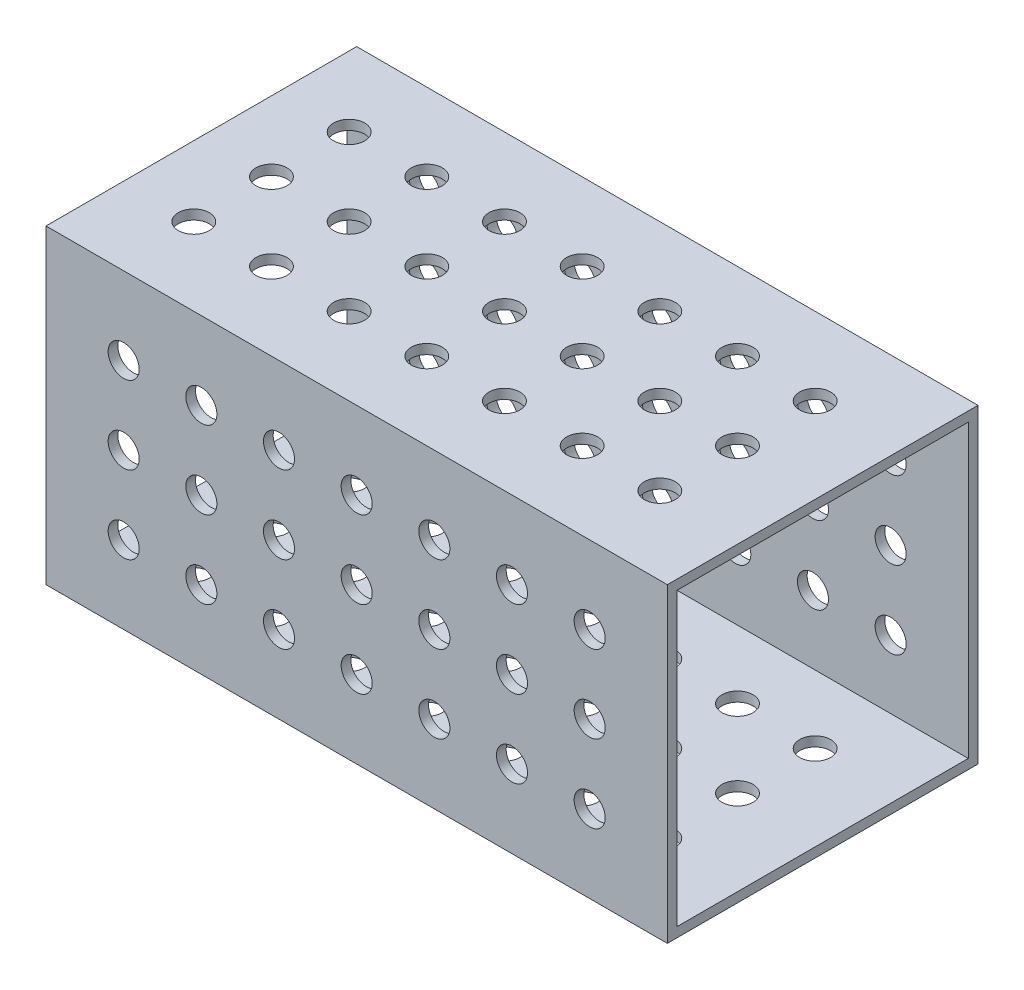
SolidWorks part; units mm, degrees
ref_plane "Front Plane" through (0, 0, 0) normal (0, 0, 1) x (1, 0, 0)
ref_plane "Top Plane" through (0, 0, 0) normal (0, 1, 0) x (1, 0, 0)
ref_plane "Right Plane" through (0, 0, 0) normal (1, 0, 0) x (0, 0, -1)
sketch "Sketch1" plane through (0, 0, 0) normal (1, 0, 0) x (0, 0, -1)
  line L1 (-25.4, -25.4) -> (25.4, -25.4)
  line L2 (-25.4, -25.4) -> (-25.4, 25.4)
  line L3 (-25.4, 25.4) -> (25.4, 25.4)
  line L4 (25.4, -25.4) -> (25.4, 25.4)
  line L5 (-25.4, -25.4) -> (25.4, 25.4) construction
  line L6 (-25.4, 25.4) -> (25.4, -25.4) construction
  line L7 (-23.8125, -23.8125) -> (23.8125, -23.8125)
  line L8 (-23.8125, -23.8125) -> (-23.8125, 23.8125)
  line L9 (-23.8125, 23.8125) -> (23.8125, 23.8125)
  line L10 (23.8125, -23.8125) -> (23.8125, 23.8125)
  line L11 (-23.8125, -23.8125) -> (23.8125, 23.8125) construction
  line L12 (-23.8125, 23.8125) -> (23.8125, -23.8125) construction
  point P0 (0, 0)
  point P7 (0, 0)
  dimension "D1" = 50.8
  dimension "D2" = 50.8
  dimension "D3" = 47.625
extrude "Boss-Extrude1" add sketch "Sketch1" along normal blind 101.6
sketch "Sketch2" plane through (0, 0, 25.4) normal (0, 0, 1) x (1, 0, 0)
  line L0 (-1000, 0) -> (49000, 0) construction
  line L2 (-994.1549, 12.7) -> (49005.8451, 12.7) construction
  line L3 (-984.8446, -12.7) -> (49015.1554, -12.7) construction
  line L4 (101.6, 25.4) -> (0, 25.4) construction
  line L5 (101.6, -25.4) -> (0, -25.4) construction
  line L6 (0, 25.4) -> (0, -25.4) construction
  line L7 (12.7, 12.7) -> (12.7, 0) construction
  line L8 (12.7, 12.7) -> (25.4, 12.7) construction
  circle A24 centre (12.7, 12.7) radius 2.54
  circle A25 centre (12.7, 0) radius 2.54
  circle A26 centre (12.7, -12.7) radius 2.54
  circle A27 centre (25.4, 12.7) radius 2.54
  circle A28 centre (25.4, 0) radius 2.54
  circle A29 centre (25.4, -12.7) radius 2.54
  circle A30 centre (38.1, 12.7) radius 2.54
  circle A31 centre (38.1, 0) radius 2.54
  circle A32 centre (38.1, -12.7) radius 2.54
  circle A33 centre (50.8, 12.7) radius 2.54
  circle A34 centre (50.8, 0) radius 2.54
  circle A35 centre (50.8, -12.7) radius 2.54
  circle A36 centre (63.5, 12.7) radius 2.54
  circle A37 centre (63.5, 0) radius 2.54
  circle A38 centre (63.5, -12.7) radius 2.54
  circle A39 centre (76.2, 12.7) radius 2.54
  circle A40 centre (76.2, 0) radius 2.54
  circle A41 centre (76.2, -12.7) radius 2.54
  circle A42 centre (88.9, 12.7) radius 2.54
  circle A43 centre (88.9, 0) radius 2.54
  circle A44 centre (88.9, -12.7) radius 2.54
  circle A165 centre (101.6, 12.7) radius 2.54 [skipped]
  circle A166 centre (101.6, 0) radius 2.54 [skipped]
  circle A167 centre (101.6, -12.7) radius 2.54 [skipped]
  circle A168 centre (114.3, 12.7) radius 2.54 [skipped]
  circle A169 centre (114.3, 0) radius 2.54 [skipped]
  circle A170 centre (114.3, -12.7) radius 2.54 [skipped]
  circle A171 centre (127, 12.7) radius 2.54 [skipped]
  circle A172 centre (127, 0) radius 2.54 [skipped]
  circle A173 centre (127, -12.7) radius 2.54 [skipped]
  circle A174 centre (139.7, 12.7) radius 2.54 [skipped]
  circle A175 centre (139.7, 0) radius 2.54 [skipped]
  circle A176 centre (139.7, -12.7) radius 2.54 [skipped]
  circle A177 centre (152.4, 12.7) radius 2.54 [skipped]
  circle A178 centre (152.4, 0) radius 2.54 [skipped]
  circle A179 centre (152.4, -12.7) radius 2.54 [skipped]
  circle A180 centre (165.1, 12.7) radius 2.54 [skipped]
  circle A181 centre (165.1, 0) radius 2.54 [skipped]
  circle A182 centre (165.1, -12.7) radius 2.54 [skipped]
  circle A183 centre (177.8, 12.7) radius 2.54 [skipped]
  circle A184 centre (177.8, 0) radius 2.54 [skipped]
  circle A185 centre (177.8, -12.7) radius 2.54 [skipped]
  circle A186 centre (190.5, 12.7) radius 2.54 [skipped]
  circle A187 centre (190.5, 0) radius 2.54 [skipped]
  circle A188 centre (190.5, -12.7) radius 2.54 [skipped]
  circle A189 centre (203.2, 12.7) radius 2.54 [skipped]
  circle A190 centre (203.2, 0) radius 2.54 [skipped]
  circle A191 centre (203.2, -12.7) radius 2.54 [skipped]
  circle A192 centre (215.9, 12.7) radius 2.54 [skipped]
  circle A193 centre (215.9, 0) radius 2.54 [skipped]
  circle A194 centre (215.9, -12.7) radius 2.54 [skipped]
  circle A195 centre (228.6, 12.7) radius 2.54 [skipped]
  circle A196 centre (228.6, 0) radius 2.54 [skipped]
  circle A197 centre (228.6, -12.7) radius 2.54 [skipped]
  circle A198 centre (241.3, 12.7) radius 2.54 [skipped]
  circle A199 centre (241.3, 0) radius 2.54 [skipped]
  circle A200 centre (241.3, -12.7) radius 2.54 [skipped]
  circle A201 centre (254, 12.7) radius 2.54 [skipped]
  circle A202 centre (254, 0) radius 2.54 [skipped]
  circle A203 centre (254, -12.7) radius 2.54 [skipped]
  circle A204 centre (266.7, 12.7) radius 2.54 [skipped]
  circle A205 centre (266.7, 0) radius 2.54 [skipped]
  circle A206 centre (266.7, -12.7) radius 2.54 [skipped]
  circle A207 centre (279.4, 12.7) radius 2.54 [skipped]
  circle A208 centre (279.4, 0) radius 2.54 [skipped]
  circle A209 centre (279.4, -12.7) radius 2.54 [skipped]
  circle A210 centre (292.1, 12.7) radius 2.54 [skipped]
  circle A211 centre (292.1, 0) radius 2.54 [skipped]
  circle A212 centre (292.1, -12.7) radius 2.54 [skipped]
  circle A213 centre (304.8, 12.7) radius 2.54 [skipped]
  circle A214 centre (304.8, 0) radius 2.54 [skipped]
  circle A215 centre (304.8, -12.7) radius 2.54 [skipped]
  circle A216 centre (317.5, 12.7) radius 2.54 [skipped]
  circle A217 centre (317.5, 0) radius 2.54 [skipped]
  circle A218 centre (317.5, -12.7) radius 2.54 [skipped]
  circle A219 centre (330.2, 12.7) radius 2.54 [skipped]
  circle A220 centre (330.2, 0) radius 2.54 [skipped]
  circle A221 centre (330.2, -12.7) radius 2.54 [skipped]
  circle A222 centre (342.9, 12.7) radius 2.54 [skipped]
  circle A223 centre (342.9, 0) radius 2.54 [skipped]
  circle A224 centre (342.9, -12.7) radius 2.54 [skipped]
  circle A225 centre (355.6, 12.7) radius 2.54 [skipped]
  circle A226 centre (355.6, 0) radius 2.54 [skipped]
  circle A227 centre (355.6, -12.7) radius 2.54 [skipped]
  circle A228 centre (368.3, 12.7) radius 2.54 [skipped]
  circle A229 centre (368.3, 0) radius 2.54 [skipped]
  circle A230 centre (368.3, -12.7) radius 2.54 [skipped]
  circle A231 centre (381, 12.7) radius 2.54 [skipped]
  circle A232 centre (381, 0) radius 2.54 [skipped]
  circle A233 centre (381, -12.7) radius 2.54 [skipped]
  circle A234 centre (393.7, 12.7) radius 2.54 [skipped]
  circle A235 centre (393.7, 0) radius 2.54 [skipped]
  circle A236 centre (393.7, -12.7) radius 2.54 [skipped]
  circle A237 centre (406.4, 12.7) radius 2.54 [skipped]
  circle A238 centre (406.4, 0) radius 2.54 [skipped]
  circle A239 centre (406.4, -12.7) radius 2.54 [skipped]
  circle A240 centre (419.1, 12.7) radius 2.54 [skipped]
  circle A241 centre (419.1, 0) radius 2.54 [skipped]
  circle A242 centre (419.1, -12.7) radius 2.54 [skipped]
  circle A243 centre (431.8, 12.7) radius 2.54 [skipped]
  circle A244 centre (431.8, 0) radius 2.54 [skipped]
  circle A245 centre (431.8, -12.7) radius 2.54 [skipped]
  circle A246 centre (444.5, 12.7) radius 2.54 [skipped]
  circle A247 centre (444.5, 0) radius 2.54 [skipped]
  circle A248 centre (444.5, -12.7) radius 2.54 [skipped]
  circle A249 centre (457.2, 12.7) radius 2.54 [skipped]
  circle A250 centre (457.2, 0) radius 2.54 [skipped]
  circle A251 centre (457.2, -12.7) radius 2.54 [skipped]
  circle A252 centre (469.9, 12.7) radius 2.54 [skipped]
  circle A253 centre (469.9, 0) radius 2.54 [skipped]
  circle A254 centre (469.9, -12.7) radius 2.54 [skipped]
  circle A255 centre (482.6, 12.7) radius 2.54 [skipped]
  circle A256 centre (482.6, 0) radius 2.54 [skipped]
  circle A257 centre (482.6, -12.7) radius 2.54 [skipped]
  circle A258 centre (495.3, 12.7) radius 2.54 [skipped]
  circle A259 centre (495.3, 0) radius 2.54 [skipped]
  circle A260 centre (495.3, -12.7) radius 2.54 [skipped]
  circle A261 centre (508, 12.7) radius 2.54 [skipped]
  circle A262 centre (508, 0) radius 2.54 [skipped]
  circle A263 centre (508, -12.7) radius 2.54 [skipped]
  circle A264 centre (520.7, 12.7) radius 2.54 [skipped]
  circle A265 centre (520.7, 0) radius 2.54 [skipped]
  circle A266 centre (520.7, -12.7) radius 2.54 [skipped]
  circle A267 centre (533.4, 12.7) radius 2.54 [skipped]
  circle A268 centre (533.4, 0) radius 2.54 [skipped]
  circle A269 centre (533.4, -12.7) radius 2.54 [skipped]
  circle A270 centre (546.1, 12.7) radius 2.54 [skipped]
  circle A271 centre (546.1, 0) radius 2.54 [skipped]
  circle A272 centre (546.1, -12.7) radius 2.54 [skipped]
  circle A273 centre (558.8, 12.7) radius 2.54 [skipped]
  circle A274 centre (558.8, 0) radius 2.54 [skipped]
  circle A275 centre (571.5, 12.7) radius 2.54 [skipped]
  circle A276 centre (571.5, 0) radius 2.54 [skipped]
  circle A277 centre (571.5, -12.7) radius 2.54 [skipped]
  circle A278 centre (584.2, 12.7) radius 2.54 [skipped]
  circle A279 centre (584.2, 0) radius 2.54 [skipped]
  circle A280 centre (584.2, -12.7) radius 2.54 [skipped]
  circle A281 centre (596.9, 12.7) radius 2.54 [skipped]
  circle A282 centre (596.9, 0) radius 2.54 [skipped]
  circle A283 centre (596.9, -12.7) radius 2.54 [skipped]
  circle A284 centre (558.8, -12.7) radius 2.54 [skipped]
  dimension "D1" = 12.7
  dimension "D3" = 5.08
  dimension "D2" = 12.7
  dimension "D4" = 12.7
  dimension "D6" = 12.7
  dimension "D8" = 12.7
  dimension "D5" = 3
  dimension "D7" = 47
extrude "Cut-Extrude2" cut sketch "Sketch2" against normal blind 609.6
sketch "Sketch3" plane through (0, -25.4, 0) normal (0, -1, 0) x (1, 0, 0)
  line L0 (11.4669, 12.7) -> (11.4669, 0) construction
  line L1 (11.4669, 12.7) -> (24.1669, 12.7) construction
  line L2 (101.6, 25.4) -> (0, 25.4) construction
  line L3 (101.6, -25.4) -> (0, -25.4) construction
  circle A0 centre (11.4669, 12.7) radius 2.54
  circle A1 centre (11.4669, 0) radius 2.54
  circle A2 centre (11.4712, -12.7) radius 2.54
  circle A3 centre (24.1669, 12.7) radius 2.54
  circle A4 centre (24.1669, 0) radius 2.54
  circle A5 centre (24.1712, -12.7) radius 2.54
  circle A6 centre (36.8669, 12.7) radius 2.54
  circle A7 centre (36.8712, 0) radius 2.54
  circle A8 centre (36.8712, -12.7) radius 2.54
  circle A9 centre (49.5669, 12.7) radius 2.54
  circle A10 centre (49.5712, 0) radius 2.54
  circle A11 centre (49.5712, -12.7) radius 2.54
  circle A12 centre (62.2669, 12.7) radius 2.54
  circle A13 centre (62.2712, 0) radius 2.54
  circle A14 centre (62.2712, -12.7) radius 2.54
  circle A15 centre (74.9669, 12.7) radius 2.54
  circle A16 centre (74.9712, 0) radius 2.54
  circle A17 centre (74.9712, -12.7) radius 2.54
  circle A18 centre (87.6712, 12.7) radius 2.54
  circle A19 centre (87.6712, 0) radius 2.54
  circle A20 centre (87.6712, -12.7) radius 2.54
  dimension "D1" = 5.08
  dimension "D4" = 12.7
  dimension "D5" = 12.7
  dimension "D6" = 12.7
  dimension "D7" = 12.7
  dimension "D8" = 12.7
  dimension "D9" = 12.7
  dimension "D10" = 12.7
  dimension "D11" = 12.7
  dimension "D12" = 12.7
  dimension "D13" = 12.7
  dimension "D14" = 12.7
  dimension "D15" = 12.7
  dimension "D16" = 12.7
  dimension "D17" = 12.7
  dimension "D18" = 12.7
  dimension "D19" = 12.7
  dimension "D20" = 12.7
  dimension "D21" = 12.7
  dimension "D22" = 12.7
  dimension "D23" = 12.7
  dimension "D24" = 12.7
  dimension "D25" = 12.7
  dimension "D26" = 12.7
  dimension "D27" = 12.7
  dimension "D28" = 12.7
  dimension "D29" = 5.08
  dimension "D31" = 12.7
  dimension "D2" = 12.7
  dimension "D3" = 12.7
  dimension "D30" = 12.7
extrude "Cut-Extrude3" cut sketch "Sketch3" against normal blind 76.2
